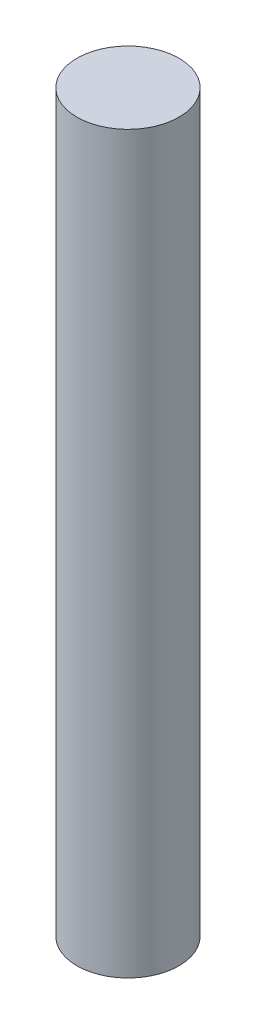
SolidWorks part; units mm, degrees
ref_plane "Front Plane" through (0, 0, 0) normal (0, 0, 1) x (1, 0, 0)
ref_plane "Top Plane" through (0, 0, 0) normal (0, 1, 0) x (1, 0, 0)
ref_plane "Right Plane" through (0, 0, 0) normal (1, 0, 0) x (0, 0, -1)
sketch "Sketch1" plane through (0, 0, 0) normal (0, 1, 0) x (1, 0, 0)
  circle A0 centre (0, 0) radius 2.5
  dimension "D1" = 5
extrude "Boss-Extrude1" add sketch "Sketch1" along normal blind 36
